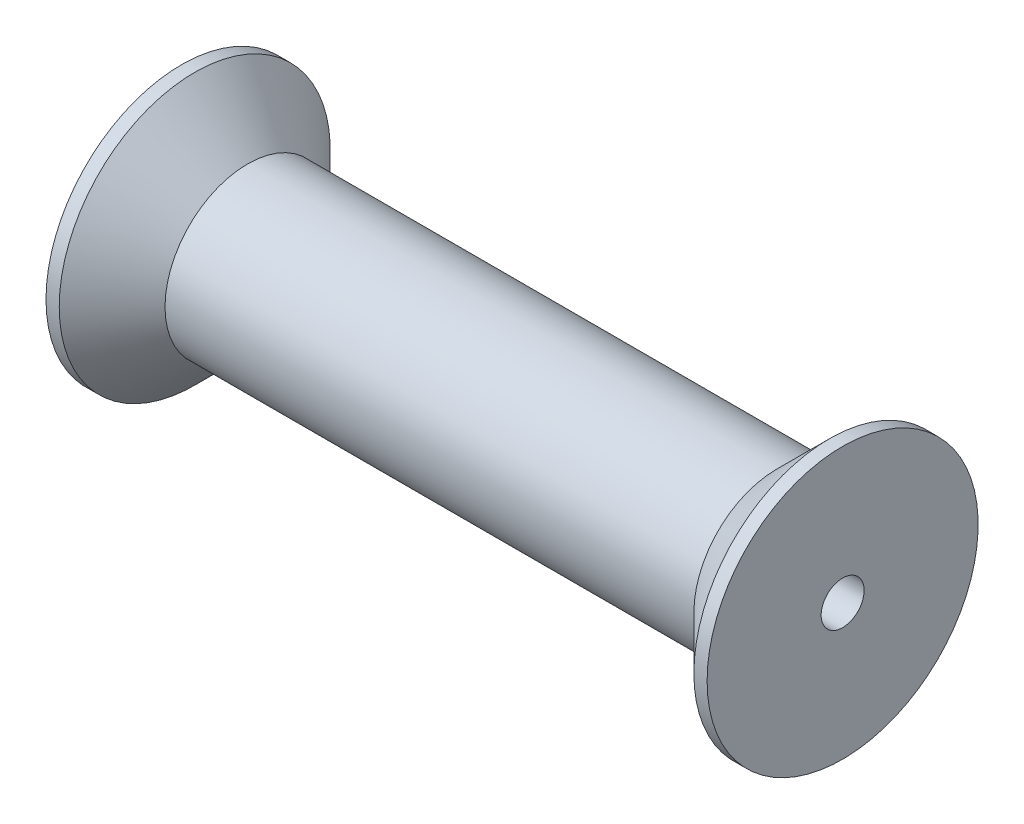
SolidWorks part; units mm, degrees
ref_plane "Front Plane" through (0, 0, 0) normal (0, 0, 1) x (1, 0, 0)
ref_plane "Top Plane" through (0, 0, 0) normal (0, 1, 0) x (1, 0, 0)
ref_plane "Right Plane" through (0, 0, 0) normal (1, 0, 0) x (0, 0, -1)
sketch "Sketch1" plane through (0, 0, 0) normal (0, 0, 1) x (1, 0, 0)
  line L0 (0, 0) -> (100, 0) construction
  line L1 (0, 3.25) -> (10, 3.25)
  line L2 (0, 3.25) -> (0, 20.5)
  line L3 (0, 20.5) -> (2, 20.5)
  line L4 (2, 20.5) -> (10, 12.5)
  line L5 (10, 12.5) -> (90, 12.5)
  line L6 (90, 12.5) -> (98, 20.5)
  line L7 (98, 20.5) -> (100, 20.5)
  line L8 (100, 20.5) -> (100, 3.25)
  line L9 (100, 3.25) -> (90, 3.25)
  line L10 (10, 3.25) -> (32.5267, 16.2558) construction
  line L11 (68.5407, 9) -> (31.4593, 9)
  arc A0 (10, 3.25) -> (31.4593, 9) centre (31.4593, -33.9186) cw
  arc A1 (90, 3.25) -> (68.5407, 9) centre (68.5407, -33.9186) ccw
  dimension "D1" = 30
  dimension "D2" = 10
  dimension "D3" = 6.5
  dimension "D4" = 18
  dimension "D5" = 45
  dimension "D6" = 100
  dimension "D7" = 25
  dimension "D8" = 2
revolve "Revolve1" add sketch "Sketch1" angle 360 about L0
